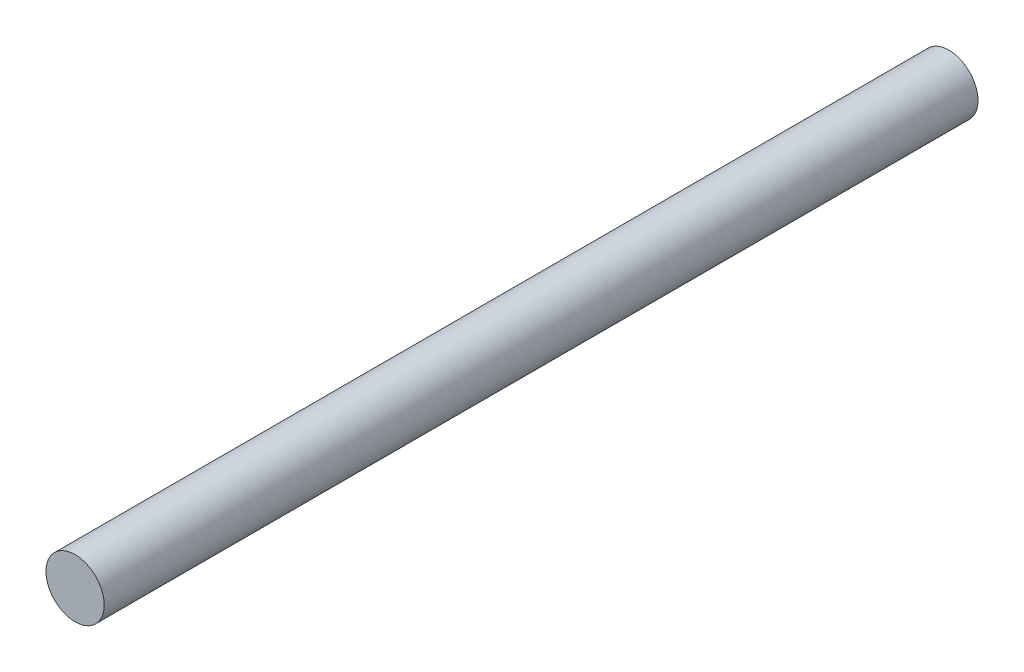
SolidWorks part; units mm, degrees
ref_plane "Front Plane" through (0, 0, 0) normal (0, 0, 1) x (1, 0, 0)
ref_plane "Top Plane" through (0, 0, 0) normal (0, 1, 0) x (1, 0, 0)
ref_plane "Right Plane" through (0, 0, 0) normal (1, 0, 0) x (0, 0, -1)
sketch "Sketch1" plane through (0, 0, 0) normal (0, 0, 1) x (1, 0, 0)
  circle A0 centre (0, 0) radius 5
  dimension "D1" = 10
extrude "Boss-Extrude1" add sketch "Sketch1" along normal blind 150
